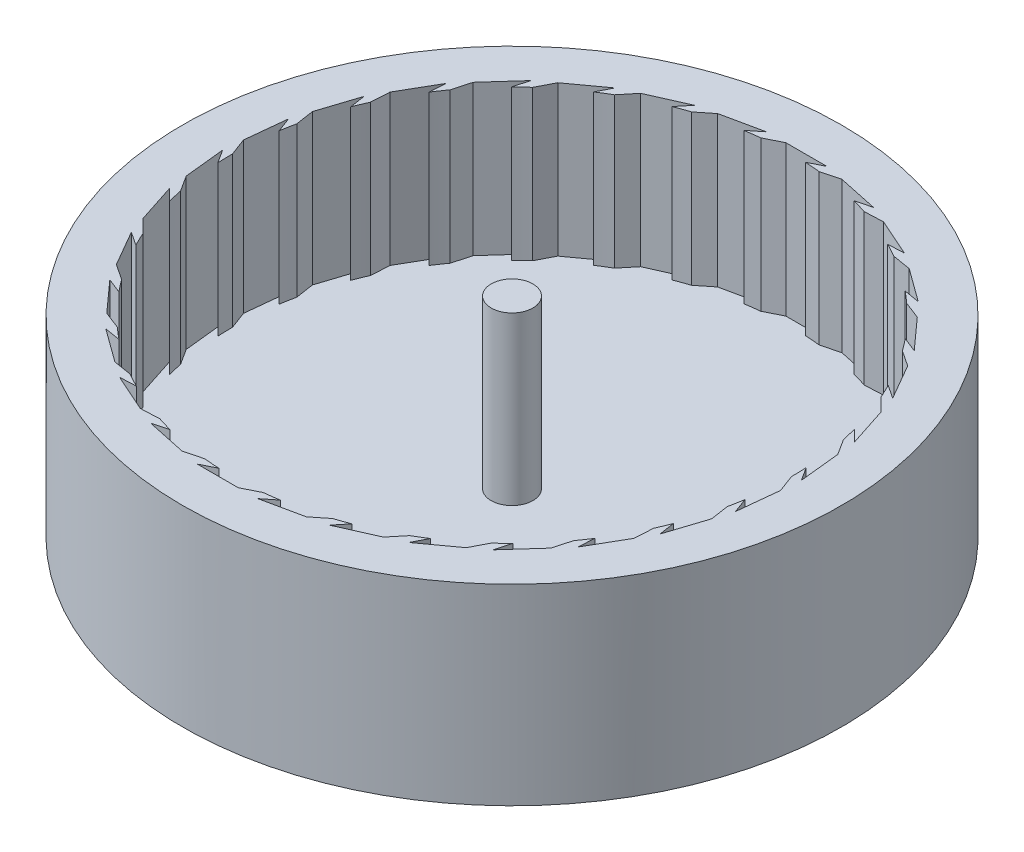
SolidWorks part; units mm, degrees
ref_plane "Front Plane" through (0, 0, 0) normal (0, 0, 1) x (1, 0, 0)
ref_plane "Top Plane" through (0, 0, 0) normal (0, 1, 0) x (1, 0, 0)
ref_plane "Right Plane" through (0, 0, 0) normal (1, 0, 0) x (0, 0, -1)
sketch "Sketch1" plane through (0, 0, 0) normal (0, 1, 0) x (1, 0, 0)
  line L0 (-3.5, 33.3167) -> (3.5, 33.3167) construction
  line L1 (-3.5896, 34.3167) -> (3.4104, 34.3167) construction
  line L2 (-3.5, 33.3167) -> (-1.5, 34.3167)
  line L3 (3.4104, 34.3167) -> (1.6916, 33.4573)
  line L4 (-1.5, 34.3167) -> (3.4104, 34.3167)
  line L5 (-3.5, 33.3167) -> (1.6916, 33.4573)
  line L6 (3.5034, 33.3163) -> (8.6108, 32.3744)
  line L7 (3.5034, 33.3163) -> (5.6676, 33.8786)
  line L8 (5.6676, 33.8786) -> (10.4707, 32.8577)
  line L9 (10.4707, 32.8577) -> (8.6108, 32.3744)
  line L10 (10.3537, 31.8599) -> (15.1537, 29.8767)
  line L11 (10.3537, 31.8599) -> (12.5875, 31.9599)
  line L12 (12.5875, 31.9599) -> (17.0734, 29.9627)
  line L13 (17.0734, 29.9627) -> (15.1537, 29.8767)
  line L14 (16.7515, 29.011) -> (21.0342, 26.0732)
  line L15 (16.7515, 29.011) -> (18.9573, 28.6444)
  line L16 (18.9573, 28.6444) -> (22.9299, 25.7582)
  line L17 (22.9299, 25.7582) -> (21.0342, 26.0732)
  line L18 (22.4171, 24.8942) -> (25.9955, 21.1302)
  line L19 (22.4171, 24.8942) -> (24.4986, 24.077)
  line L20 (24.4986, 24.077) -> (27.7843, 20.4279)
  line L21 (27.7843, 20.4279) -> (25.9955, 21.1302)
  line L22 (27.1031, 19.6894) -> (29.8206, 15.2637)
  line L23 (27.1031, 19.6894) -> (28.9691, 18.4574)
  line L24 (28.9691, 18.4574) -> (31.4243, 14.2048)
  line L25 (31.4243, 14.2048) -> (29.8206, 15.2637)
  line L26 (30.6045, 13.6241) -> (32.3425, 8.7301)
  line L27 (30.6045, 13.6241) -> (32.1736, 12.031)
  line L28 (32.1736, 12.031) -> (33.691, 7.3609)
  line L29 (33.691, 7.3609) -> (32.3425, 8.7301)
  line L30 (32.7683, 6.9634) -> (33.4508, 1.8149)
  line L31 (32.7683, 6.9634) -> (33.9719, 5.0789)
  line L32 (33.9719, 5.0789) -> (34.4852, 0.1953)
  line L33 (34.4852, 0.1953) -> (33.4508, 1.8149)
  line L34 (33.5, -0.0017) -> (33.0972, -5.1796)
  line L35 (33.5, -0.0017) -> (34.2855, -2.0953)
  line L36 (34.2855, -2.0953) -> (33.7722, -6.9788)
  line L37 (33.7722, -6.9788) -> (33.0972, -5.1796)
  line L38 (32.7676, -6.9667) -> (31.297, -11.9477)
  line L39 (32.7676, -6.9667) -> (33.1006, -9.1778)
  line L40 (33.1006, -9.1778) -> (31.5832, -13.8479)
  line L41 (31.5832, -13.8479) -> (31.297, -11.9477)
  line L42 (30.6031, -13.6272) -> (28.129, -18.1936)
  line L43 (30.6031, -13.6272) -> (30.4691, -15.8593)
  line L44 (30.4691, -15.8593) -> (28.0139, -20.1118)
  line L45 (28.0139, -20.1118) -> (28.129, -18.1936)
  line L46 (27.1011, -19.6922) -> (23.7317, -23.6444)
  line L47 (27.1011, -19.6922) -> (26.5059, -21.8476)
  line L48 (26.5059, -21.8476) -> (23.2202, -25.4968)
  line L49 (23.2202, -25.4968) -> (23.7317, -23.6444)
  line L50 (22.4146, -24.8965) -> (18.2972, -28.0618)
  line L51 (22.4146, -24.8965) -> (21.3844, -26.8811)
  line L52 (21.3844, -26.8811) -> (17.4118, -29.7673)
  line L53 (17.4118, -29.7673) -> (18.2972, -28.0618)
  line L54 (16.7485, -29.0127) -> (12.0629, -31.2528)
  line L55 (16.7485, -29.0127) -> (15.3282, -30.7397)
  line L56 (15.3282, -30.7397) -> (10.8423, -32.737)
  line L57 (10.8423, -32.737) -> (12.0629, -31.2528)
  line L58 (10.3504, -31.8609) -> (5.3015, -33.0778)
  line L59 (10.3504, -31.8609) -> (8.6021, -33.2549)
  line L60 (8.6021, -33.2549) -> (3.799, -34.2758)
  line L61 (3.799, -34.2758) -> (5.3015, -33.0778)
  line L62 (3.5, -33.3167) -> (-1.6916, -33.4573)
  line L63 (3.5, -33.3167) -> (1.5, -34.3167)
  line L64 (1.5, -34.3167) -> (-3.4104, -34.3167)
  line L65 (-3.4104, -34.3167) -> (-1.6916, -33.4573)
  line L66 (-3.5034, -33.3163) -> (-8.6108, -32.3744)
  line L67 (-3.5034, -33.3163) -> (-5.6676, -33.8786)
  line L68 (-5.6676, -33.8786) -> (-10.4707, -32.8577)
  line L69 (-10.4707, -32.8577) -> (-8.6108, -32.3744)
  line L70 (-10.3537, -31.8599) -> (-15.1537, -29.8767)
  line L71 (-10.3537, -31.8599) -> (-12.5875, -31.9599)
  line L72 (-12.5875, -31.9599) -> (-17.0734, -29.9627)
  line L73 (-17.0734, -29.9627) -> (-15.1537, -29.8767)
  line L74 (-16.7515, -29.011) -> (-21.0342, -26.0732)
  line L75 (-16.7515, -29.011) -> (-18.9573, -28.6444)
  line L76 (-18.9573, -28.6444) -> (-22.9299, -25.7582)
  line L77 (-22.9299, -25.7582) -> (-21.0342, -26.0732)
  line L78 (-22.4171, -24.8942) -> (-25.9955, -21.1302)
  line L79 (-22.4171, -24.8942) -> (-24.4986, -24.077)
  line L80 (-24.4986, -24.077) -> (-27.7843, -20.4279)
  line L81 (-27.7843, -20.4279) -> (-25.9955, -21.1302)
  line L82 (-27.1031, -19.6894) -> (-29.8206, -15.2637)
  line L83 (-27.1031, -19.6894) -> (-28.9691, -18.4574)
  line L84 (-28.9691, -18.4574) -> (-31.4243, -14.2048)
  line L85 (-31.4243, -14.2048) -> (-29.8206, -15.2637)
  line L86 (-30.6045, -13.6241) -> (-32.3425, -8.7301)
  line L87 (-30.6045, -13.6241) -> (-32.1736, -12.031)
  line L88 (-32.1736, -12.031) -> (-33.691, -7.3609)
  line L89 (-33.691, -7.3609) -> (-32.3425, -8.7301)
  line L90 (-32.7683, -6.9634) -> (-33.4508, -1.8149)
  line L91 (-32.7683, -6.9634) -> (-33.9719, -5.0789)
  line L92 (-33.9719, -5.0789) -> (-34.4852, -0.1953)
  line L93 (-34.4852, -0.1953) -> (-33.4508, -1.8149)
  line L94 (-33.5, 0.0017) -> (-33.0972, 5.1796)
  line L95 (-33.5, 0.0017) -> (-34.2855, 2.0953)
  line L96 (-34.2855, 2.0953) -> (-33.7722, 6.9788)
  line L97 (-33.7722, 6.9788) -> (-33.0972, 5.1796)
  line L98 (-32.7676, 6.9667) -> (-31.297, 11.9477)
  line L99 (-32.7676, 6.9667) -> (-33.1006, 9.1778)
  line L100 (-33.1006, 9.1778) -> (-31.5832, 13.8479)
  line L101 (-31.5832, 13.8479) -> (-31.297, 11.9477)
  line L102 (-30.6031, 13.6272) -> (-28.129, 18.1936)
  line L103 (-30.6031, 13.6272) -> (-30.4691, 15.8593)
  line L104 (-30.4691, 15.8593) -> (-28.0139, 20.1118)
  line L105 (-28.0139, 20.1118) -> (-28.129, 18.1936)
  line L106 (-27.1011, 19.6922) -> (-23.7317, 23.6444)
  line L107 (-27.1011, 19.6922) -> (-26.5059, 21.8476)
  line L108 (-26.5059, 21.8476) -> (-23.2202, 25.4968)
  line L109 (-23.2202, 25.4968) -> (-23.7317, 23.6444)
  line L110 (-22.4146, 24.8965) -> (-18.2972, 28.0618)
  line L111 (-22.4146, 24.8965) -> (-21.3844, 26.8811)
  line L112 (-21.3844, 26.8811) -> (-17.4118, 29.7673)
  line L113 (-17.4118, 29.7673) -> (-18.2972, 28.0618)
  line L114 (-16.7485, 29.0127) -> (-12.0629, 31.2528)
  line L115 (-16.7485, 29.0127) -> (-15.3282, 30.7397)
  line L116 (-15.3282, 30.7397) -> (-10.8423, 32.737)
  line L117 (-10.8423, 32.737) -> (-12.0629, 31.2528)
  line L118 (-10.3504, 31.8609) -> (-5.3015, 33.0778)
  line L119 (-10.3504, 31.8609) -> (-8.6021, 33.2549)
  line L120 (-8.6021, 33.2549) -> (-3.799, 34.2758)
  line L121 (-3.799, 34.2758) -> (-5.3015, 33.0778)
  circle A0 centre (0, 0) radius 33.5
  circle A1 centre (0, 0) radius 39.5
  point P6 (0, 33.3167)
  point P129 (0, 0)
  dimension "D1" = 1
  dimension "D2" = 30
extrude "Boss-Extrude1" add sketch "Sketch1" along normal blind 18 contours A1 A0 L63 L64 L65 L67 L68 L69 L71 L72 L73 L75 L76 L77 L79 L80 L81 L83 L84 L85 L87 L88 L89 L91 L92 L93 L95 L96 L97 L99 L100 L101 L103 L104 L105 L107 L108 L109
sketch "Sketch2" plane through (0, 0, 0) normal (0, -1, 0) x (-1, 0, 0)
  circle A0 centre (0, 0) radius 39.5
  circle A1 centre (0, 0) radius 39.5 construction
extrude "Boss-Extrude2" add sketch "Sketch2" along normal blind 5
sketch "Sketch3" plane through (0, 0, 0) normal (0, 1, 0) x (1, 0, 0)
  circle A0 centre (0, 0) radius 2.5
extrude "Boss-Extrude3" add sketch "Sketch3" along normal blind 20
